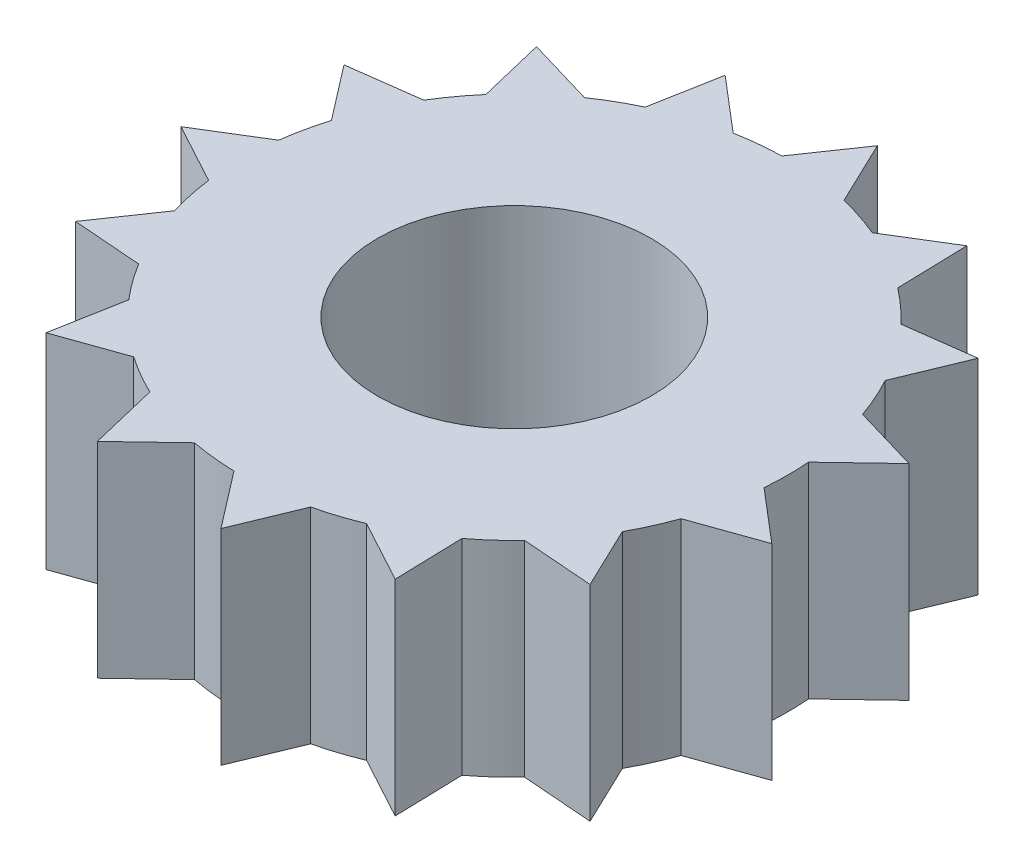
SolidWorks part; units mm, degrees
ref_plane "前视基准面" through (0, 0, 0) normal (0, 0, 1) x (1, 0, 0)
ref_plane "上视基准面" through (0, 0, 0) normal (0, 1, 0) x (1, 0, 0)
ref_plane "右视基准面" through (0, 0, 0) normal (1, 0, 0) x (0, 0, -1)
other "Configuration Table"
sketch "草图9" plane through (0, 0, 0) normal (0, 0, 1) x (1, 0, 0)
  line L0 (0, 0) -> (0, 121.5663) construction
  line L2 (-35, 80.8927) -> (-65, 80.8927)
  line L3 (-35, 80.8927) -> (-35, 40.8927)
  line L4 (-35, 40.8927) -> (-65, 40.8927)
  line L5 (-65, 80.8927) -> (-65, 40.8927)
  line L6 (-35, 80.8927) -> (-65, 40.8927) construction
  line L7 (-35, 40.8927) -> (-65, 80.8927) construction
  point P3 (-50, 60.8927)
  dimension "D1" = 50
  dimension "D2" = 40
  dimension "D3" = 30
sketch "草图16" plane through (0, 0, 0) normal (0, 0, 1) x (1, 0, 0)
  line L0 (-0.1512, 0) -> (-0.1512, 30) construction
  line L1 (-0.1512, 0) -> (30, 0) construction
  line L2 (-40.1512, 30) -> (-20.1512, 30)
  line L3 (-40.1512, 30) -> (-40.1512, 0)
  line L4 (-40.1512, 0) -> (-20.1512, 0)
  line L5 (-20.1512, 30) -> (-20.1512, 0)
  line L6 (-40.1512, 30) -> (-20.1512, 0) construction
  line L7 (-40.1512, 0) -> (-20.1512, 30) construction
  point P2 (-161.7393, 19.0616)
  point P3 (0, 0)
  point P4 (-30.1512, 15)
  point P17 (0, 0)
  point P18 (-182.4819, -1.8679)
  point P19 (0, -1.3073)
  dimension "D1" = 30
  dimension "D2" = 30
  dimension "D3" = 20
revolve "旋转5" add sketch "草图16" angle 360 about L0
sketch "草图17" plane through (0, 30, 0) normal (0, 1, 0) x (1, 0, 0)
  line L0 (-39.5294, -5.1942) -> (-48.6676, -0.2452)
  line L1 (-30.6743, 0.2452) -> (-39.8125, 5.1942)
  line L2 (-39.8125, 5.1942) -> (-39.5294, -5.1942)
  line L3 (-39.5294, -5.1942) -> (-30.6743, 0.2452)
  line L4 (-48.6676, -0.2452) -> (-39.8125, 5.1942)
  line L5 (0, 0) -> (0, 30) construction
  line L6 (-37.0345, 0) -> (-1046.6337, 0) construction
  line L7 (-63.6378, 0) -> (63.6378, 0) construction
  circle A0 centre (-36.6721, 0.0817) radius 3 construction
  circle A1 centre (-0.1512, 0) radius 40 construction
  point P8 (0, 0)
  point P9 (-39.671, 0)
  point P14 (0, 0)
  circle M6 centre (-0.1512, 0) radius 40
extrude "凸台-拉伸2" add sketch "草图17" against normal through all contours L4 L0 M6
pattern_circular "阵列(圆周)3" count 15 over 360 about axis through (-0.1512, 0, 0) along (0, 1, 0) of "凸台-拉伸2"
